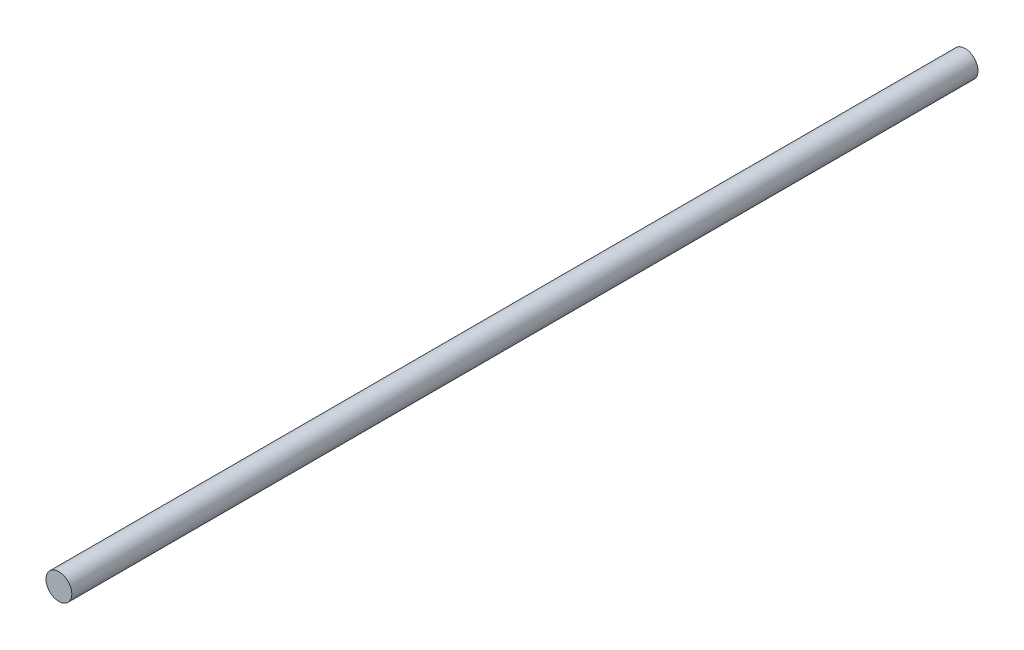
SolidWorks part; units mm, degrees
ref_plane "前视基准面" through (0, 0, 0) normal (0, 0, 1) x (1, 0, 0)
ref_plane "上视基准面" through (0, 0, 0) normal (0, 1, 0) x (1, 0, 0)
ref_plane "右视基准面" through (0, 0, 0) normal (1, 0, 0) x (0, 0, -1)
sketch "Sketch1" plane through (0, 0, 0) normal (0, 0, 1) x (1, 0, 0)
  circle A0 centre (0, 0) radius 3.6195
  dimension "D1" = 7.239
extrude "Boss-Extrude1" add sketch "Sketch1" along normal blind 254
